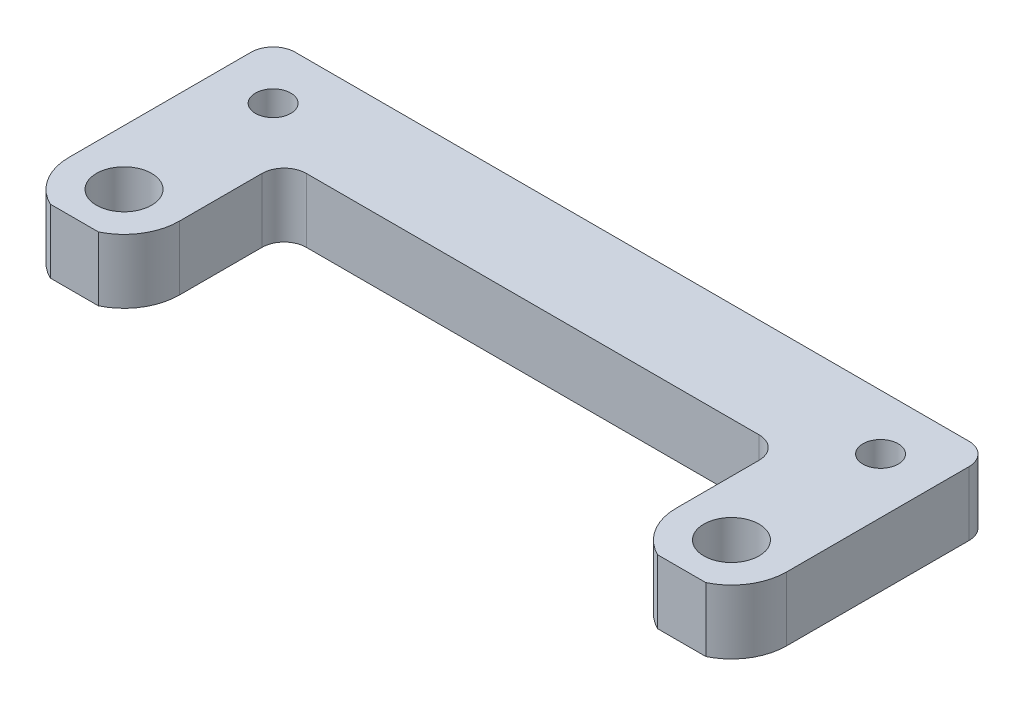
SolidWorks part; units mm, degrees
material "MC901"
ref_plane "正面" through (0, 0, 0) normal (0, 0, 1) x (1, 0, 0)
ref_plane "平面" through (0, 0, 0) normal (0, 1, 0) x (1, 0, 0)
ref_plane "右側面" through (0, 0, 0) normal (1, 0, 0) x (0, 0, -1)
sketch "ｽｹｯﾁ1" plane through (0, 0, 0) normal (0, 1, 0) x (1, 0, 0)
  line L0 (0, 0) -> (0, 11.2842) construction
  line L1 (0, 0) -> (27.5, 0) construction
  line L2 (0, -13.5) -> (27.5, -13.5) construction
  line L3 (32.5, -13.5) -> (32.5, -5)
  line L4 (-32.5, 5) -> (32.5, 5)
  line L5 (-32.5, 5) -> (-32.5, -5)
  line L7 (32.5, 5) -> (32.5, -5)
  line L8 (-32.5, 5) -> (32.5, -5) construction
  line L9 (-32.5, -5) -> (32.5, 5) construction
  line L10 (22.5, -13.5) -> (22.5, -2.5)
  line L11 (-22.5, -13.5) -> (-22.5, -2.5)
  line L12 (-32.5, -13.5) -> (-32.5, -5)
  line L14 (-22.5, -2.5) -> (-22.5, -4)
  line L15 (-22.5, -4) -> (22.5, -4)
  line L16 (22.5, -4) -> (22.5, -2.5)
  line L17 (29.6794, -18) -> (25.3206, -18)
  line L18 (-29.6794, -18) -> (-25.3206, -18)
  circle A0 centre (27.5, 0) radius 1.6
  circle A1 centre (-27.5, 0) radius 1.6
  circle A2 centre (27.5, -13.5) radius 2.5
  circle A3 centre (-27.5, -13.5) radius 2.5
  arc A4 (22.5, -13.5) -> (25.3206, -18) centre (27.5, -13.5) ccw
  arc A5 (-22.5, -13.5) -> (-25.3206, -18) centre (-27.5, -13.5) cw
  arc A6 (25.3206, -18) -> (29.6794, -18) centre (27.5, -13.5) ccw construction
  arc A7 (29.6794, -18) -> (32.5, -13.5) centre (27.5, -13.5) ccw
  arc A8 (-25.3206, -18) -> (-29.6794, -18) centre (-27.5, -13.5) cw construction
  arc A9 (-29.6794, -18) -> (-32.5, -13.5) centre (-27.5, -13.5) cw
  dimension "D1" = 3.2
  dimension "D3" = 5
  dimension "D8" = 10
  dimension "D2" = 55
  dimension "D4" = 13.5
  dimension "D5" = 55
  dimension "D6" = 65
  dimension "D7" = 10
  dimension "D9" = 9
  dimension "D10" = 4.5
extrude "ﾎﾞｽ - 押し出し1" add sketch "ｽｹｯﾁ1" along normal blind 5.8
fillet "ﾌｨﾚｯﾄ1" radius 2 4 edges at (32.5, 2.9, -5) (-32.5, 2.9, -5) (22.5, 2.9, 4) (-22.5, 2.9, 4)
